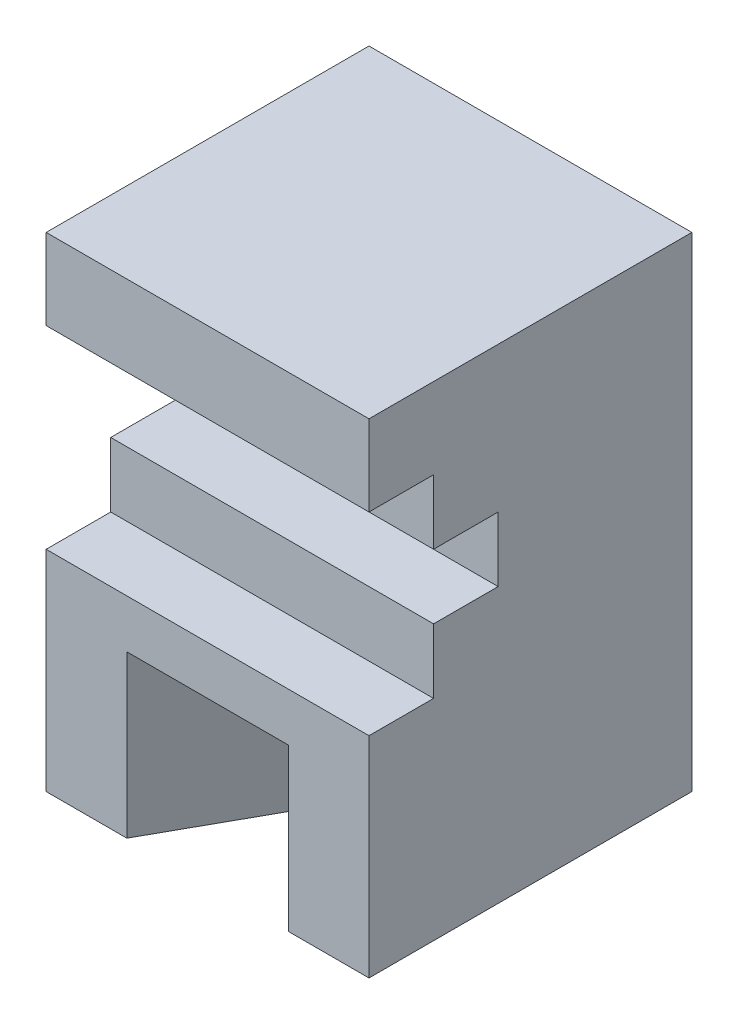
SolidWorks part; units mm, degrees
ref_plane "Front Plane" through (0, 0, 0) normal (0, 0, 1) x (1, 0, 0)
ref_plane "Top Plane" through (0, 0, 0) normal (0, 1, 0) x (1, 0, 0)
ref_plane "Right Plane" through (0, 0, 0) normal (1, 0, 0) x (0, 0, -1)
sketch "Sketch1" plane through (0, 0, 0) normal (0, 0, 1) x (1, 0, 0)
  line L1 (0, 0) -> (100, 0)
  line L2 (0, 0) -> (0, 150)
  line L3 (0, 150) -> (100, 150)
  line L4 (100, 0) -> (100, 150)
  dimension "D1" = 100
  dimension "D2" = 150
extrude "Boss-Extrude1" add sketch "Sketch1" against normal blind 100
sketch "Sketch2" plane through (0, 0, 0) normal (0, -1, 0) x (1, 0, 0)
  line L0 (25, 0) -> (50, -45)
  line L1 (100, 0) -> (0, 0) construction
  line L2 (50, -45) -> (75, 0)
  line L3 (0, 0) -> (100, 0) construction
  line L4 (75, 0) -> (25, 0)
  line L5 (100, -100) -> (100, 0) construction
  line L6 (0, -100) -> (0, 0) construction
  dimension "D1" = 25
  dimension "D2" = 25
  dimension "D3" = 50
  dimension "D4" = 45
extrude "Cut-Extrude1" cut sketch "Sketch2" against normal blind 50
sketch "Sketch3" plane through (0, 0, 0) normal (-1, 0, 0) x (0, 0, 1)
  line L0 (0, 125) -> (-20, 125)
  line L1 (0, 150) -> (0, 0) construction
  line L2 (-20, 125) -> (-20, 105)
  line L3 (-20, 105) -> (-40, 105)
  line L4 (-40, 105) -> (-40, 85)
  line L5 (-40, 85) -> (-20, 85)
  line L6 (-20, 85) -> (-20, 65)
  line L7 (-20, 65) -> (0, 65)
  line L8 (0, 65) -> (0, 125)
  line L9 (-100, 150) -> (0, 150) construction
  dimension "D1" = 25
  dimension "D2" = 20
extrude "Cut-Extrude2" cut sketch "Sketch3" against normal through all
